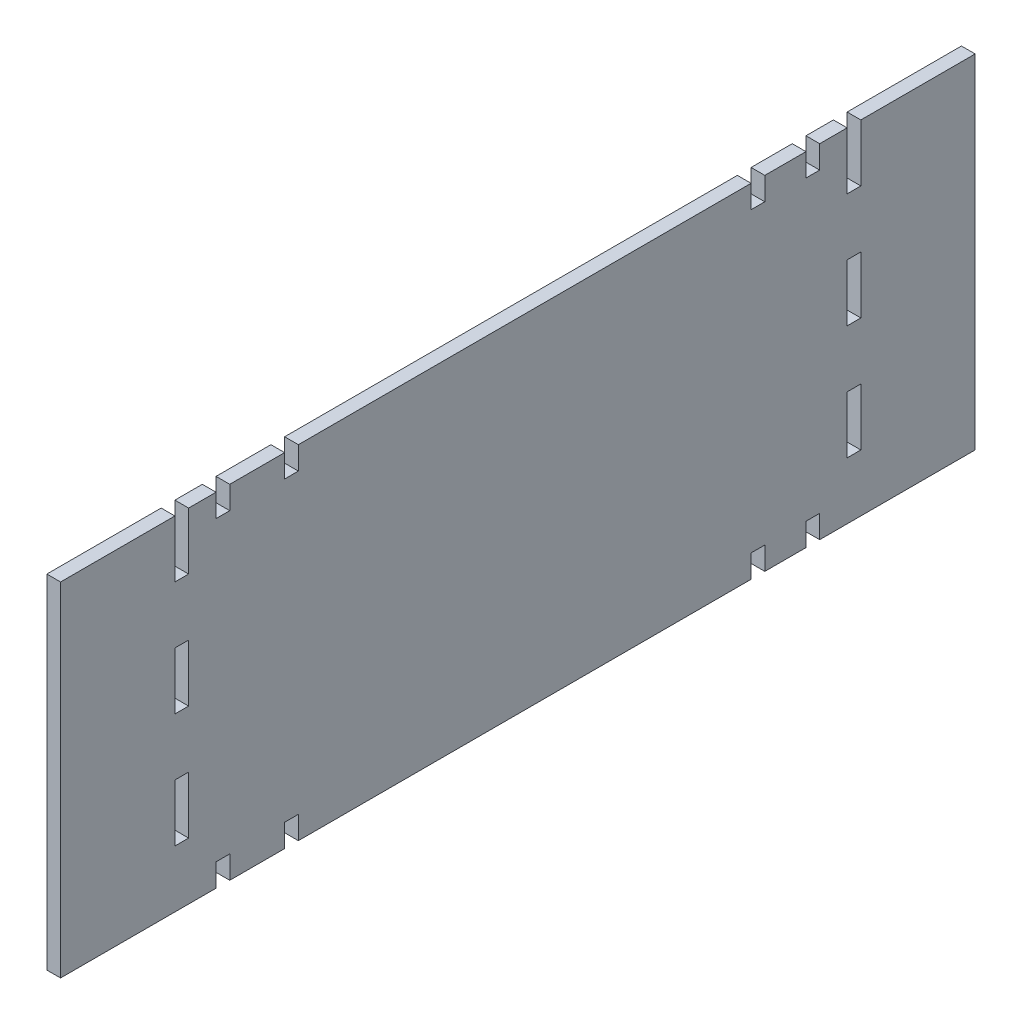
SolidWorks part; units mm, degrees
ref_plane "Front" through (0, 0, 0) normal (0, 0, 1) x (1, 0, 0)
ref_plane "Top" through (0, 0, 0) normal (0, 1, 0) x (1, 0, 0)
ref_plane "Right" through (0, 0, 0) normal (1, 0, 0) x (0, 0, -1)
sketch "Sketch1" plane through (0, 0, 0) normal (1, 0, 0) x (0, 0, -1)
  line L1 (0, 0) -> (-400, 0)
  line L2 (0, 0) -> (0, 150)
  line L3 (0, 150) -> (-400, 150)
  line L4 (-400, 0) -> (-400, 150)
  dimension "D1" = 400
  dimension "D2" = 150
extrude "Boss-Extrude1" add sketch "Sketch1" along normal blind 6
sketch "Sketch3" plane through (6, 0, 0) normal (1, 0, 0) x (0, 0, -1)
  line L0 (-400, 150) -> (-400, 0) construction
  line L1 (-350, 150) -> (-344, 150)
  line L2 (-350, 150) -> (-350, 125)
  line L3 (-350, 125) -> (-344, 125)
  line L4 (-344, 150) -> (-344, 125)
  line L5 (0, 150) -> (-400, 150) construction
  dimension "D1" = 6
  dimension "D2" = 25
  dimension "D3" = 50
extrude "Cut-Extrude1" cut sketch "Sketch3" against normal through all
pattern_linear "LPattern1" count 2 spacing 294 along (0, 0, -1) count 3 spacing 50 along (0, -1, 0) of "Cut-Extrude1"
sketch "Sketch4" plane through (6, 0, 0) normal (1, 0, 0) x (0, 0, -1)
  line L0 (-56, 150) -> (-344, 150) construction
  line L1 (-332, 150) -> (-326, 150)
  line L2 (-332, 150) -> (-332, 140)
  line L3 (-332, 140) -> (-326, 140)
  line L4 (-326, 150) -> (-326, 140)
  line L5 (-344, 125) -> (-344, 150) construction
  dimension "D1" = 6
  dimension "D2" = 12
  dimension "D3" = 10
extrude "Cut-Extrude2" cut sketch "Sketch4" against normal through all
pattern_linear "LPattern2" count 2 spacing 258 along (0, 0, -1) count 2 spacing 140 along (0, -1, 0) of "Cut-Extrude2"
sketch "Sketch5" plane through (6, 0, 0) normal (1, 0, 0) x (0, 0, -1)
  line L0 (-74, 150) -> (-326, 150) construction
  line L1 (-302, 150) -> (-296, 150)
  line L2 (-302, 150) -> (-302, 140)
  line L3 (-302, 140) -> (-296, 140)
  line L4 (-296, 150) -> (-296, 140)
  line L5 (-326, 140) -> (-326, 150) construction
  line L6 (-332, 140) -> (-326, 140) construction
  dimension "D1" = 24
  dimension "D2" = 6
extrude "Cut-Extrude3" cut sketch "Sketch5" against normal through all
pattern_linear "LPattern3" count 2 spacing 140 along (0, -1, 0) count 2 spacing 204 along (0, 0, -1) of "Cut-Extrude3"
